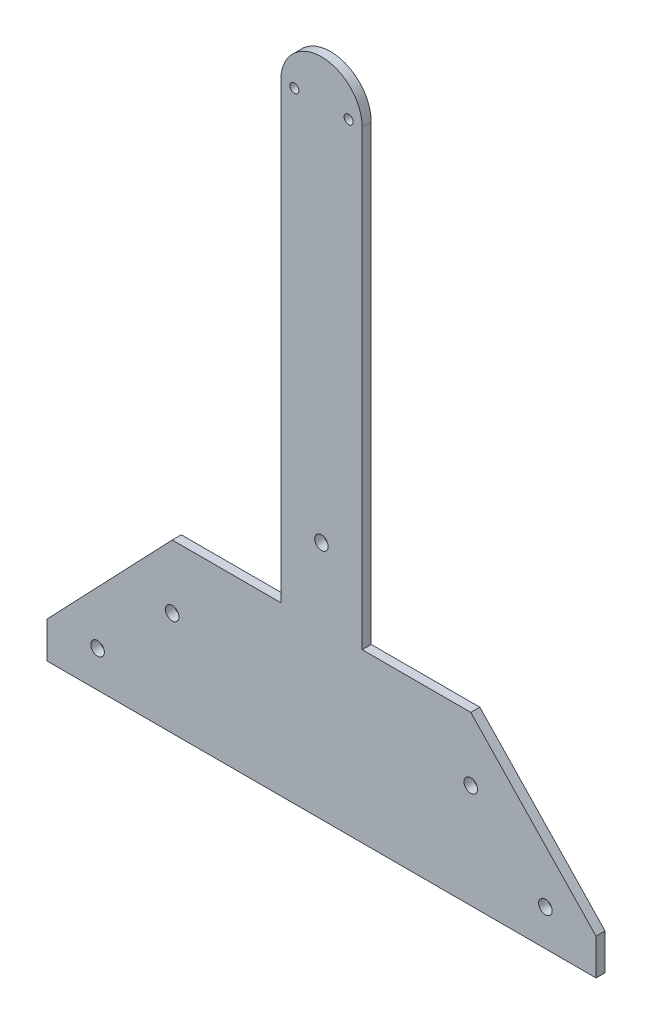
SolidWorks part; units mm, degrees
ref_plane "前视基准面" through (0, 0, 0) normal (0, 0, 1) x (1, 0, 0)
ref_plane "上视基准面" through (0, 0, 0) normal (0, 1, 0) x (1, 0, 0)
ref_plane "右视基准面" through (0, 0, 0) normal (1, 0, 0) x (0, 0, -1)
sketch "草图1" plane through (0, 0, 0) normal (0, 0, 1) x (1, 0, 0)
  line L0 (-49.7914, -7.3543) -> (-16.7914, -7.3543) construction
  line L1 (-33.2914, -7.3543) -> (-33.2914, 7.6457) construction
  line L2 (-0.2914, 7.6457) -> (-0.2914, 121.6457) construction
  line L3 (-0.2914, 121.6457) -> (5.7086, 121.6457) construction
  line L4 (-9.2914, 121.6457) -> (-9.2914, 21.6457)
  line L5 (-9.2914, 21.6457) -> (-33.2914, 21.6457)
  line L6 (-33.2914, 21.6457) -> (-60.9865, -7.3543)
  line L7 (-60.9865, -7.3543) -> (-60.9865, -15.3543)
  line L8 (-60.9865, -15.3543) -> (0, -15.3543)
  line L9 (60.4036, -15.3543) -> (-0.5829, -15.3543)
  line L10 (60.4036, -7.3543) -> (60.4036, -15.3543)
  line L11 (32.7086, 21.6457) -> (60.4036, -7.3543)
  line L12 (8.7086, 21.6457) -> (32.7086, 21.6457)
  line L13 (8.7086, 121.6457) -> (8.7086, 21.6457)
  circle A0 centre (16.2086, -7.3543) radius 2 construction
  circle A1 centre (-16.7914, -7.3543) radius 2 construction
  circle A2 centre (49.2086, -7.3543) radius 1.5
  circle A3 centre (-49.7914, -7.3543) radius 1.5
  circle A4 centre (-33.2914, 7.6457) radius 1.5
  circle A5 centre (32.7086, 7.6457) radius 1.5
  circle A6 centre (-0.2914, 7.6457) radius 2 construction
  circle A7 centre (5.7086, 121.6457) radius 1
  circle A8 centre (-6.2914, 121.6457) radius 1
  circle A9 centre (-0.2914, 121.6457) radius 1.1 construction
  circle A10 centre (-0.2914, 121.6457) radius 9 construction
  arc A11 (-9.2914, 121.6457) -> (8.7086, 121.6457) centre (-0.2914, 121.6457) cw
  circle A12 centre (-0.2914, 37.6457) radius 1.5
  dimension "D1" = 114
  dimension "D5" = 30
  dimension "D6" = 2
  dimension "D2" = 24
  dimension "D3" = 100
  dimension "D4" = 8
extrude "凸台-拉伸1" add sketch "草图1" along normal blind 2 contours A11 L4 L5 L6 L7 L8 L9 L10 L11 L12 L13 A9 A5 A4 A1 A0 A2 A3 A6 A7 A8
